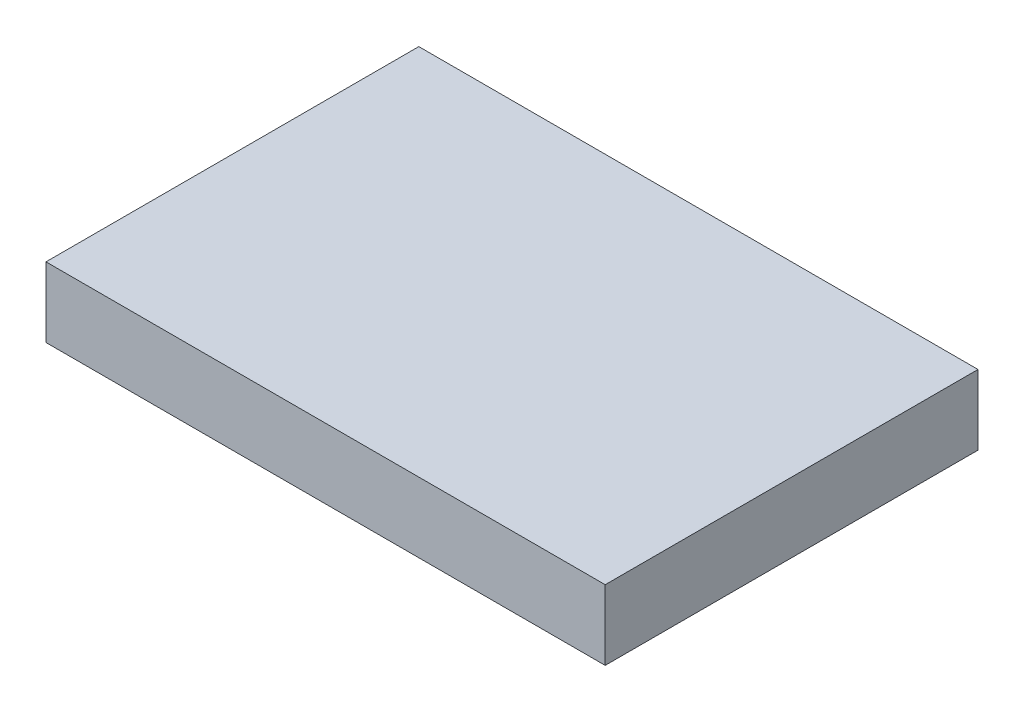
SolidWorks part; units mm, degrees
ref_plane "Front Plane" through (0, 0, 0) normal (0, 0, 1) x (1, 0, 0)
ref_plane "Top Plane" through (0, 0, 0) normal (0, 1, 0) x (1, 0, 0)
ref_plane "Right Plane" through (0, 0, 0) normal (1, 0, 0) x (0, 0, -1)
sketch "FrontSketch" plane through (0, 0, 0) normal (0, 0, 1) x (1, 0, 0)
  line L0 (152.4, 0) -> (-152.4, 0) construction
  line L1 (0, 0) -> (0, 457.2) construction
  line L2 (415.7271, 0) -> (-415.7271, 0) construction
  line L3 (-152.4, 0) -> (-152.4, 38.1) construction
  line L4 (-152.4, 38.1) -> (152.4, 38.1) construction
  line L5 (152.4, 38.1) -> (152.4, 0) construction
  line L6 (-283.3983, 169.5855) -> (472.4692, 169.5855) construction
  spline S0 degree 3 poles (152.4, 38.1) (151.3032, 71.5919) (166.4675, 141.4271) (284.1947, 294.6298) (187.3, 502.2025) (0, 457.2) knots 0 0 0 0 0.177809 0.369856 1 1 1 1
  spline S1 degree 3 poles (22.86, 38.1) (34.1821, 92.9308) (94.0071, 160.8435) (131.317, 308.4431) (55.8008, 387.2291) (0, 378.8263) knots 0 0 0 0 0.38113 0.643813 1 1 1 1
  spline S2 degree 3 poles (66.04, 38.1) (83.0873, 82.1177) (120.2069, 164.1855) (150.9401, 314.436) (52.259, 402.8065) (0, 378.8263) knots 0 0 0 0 0.326005 0.63803 1 1 1 1
  point P4 (0, 0)
  point P26 (190.3118, 169.5855)
  point P28 (116.4485, 169.5855)
  point P29 (85.9889, 169.5855)
  dimension "D1" = 38.1
  dimension "D2" = 304.8
  dimension "D3" = 457.2
  dimension "D4" = 43.18
  dimension "D5" = 86.36
sketch "TopSketch" plane through (0, 0, 0) normal (0, 1, 0) x (1, 0, 0)
  line L1 (-152.4, 101.6) -> (-152.4, -101.6) construction
  line L2 (-152.4, 101.6) -> (152.4, 101.6)
  line L3 (-152.4, 101.6) -> (-152.4, -101.6)
  line L4 (-152.4, -101.6) -> (152.4, -101.6)
  line L5 (152.4, 101.6) -> (152.4, -101.6)
  point P3 (-152.4, 0)
  point P17 (-152.4, 0)
  dimension "D3" = 203.2
extrude "Boss-Extrude1" add sketch "TopSketch" along normal blind 38.1 contours L3 L2 L5 L4
sketch "Sketch4" plane through (0, 38.1, 0) normal (0, 1, 0) x (1, 0, 0)
  line L0 (22.86, 101.6) -> (22.86, -101.6) construction
  line L3 (66.04, 101.6) -> (66.04, -101.6) construction
  arc A0 (22.86, 101.6) -> (22.86, -101.6) centre (-75.0794, 0) cw
  ellipse E0 centre (22.86, 0) end of major axis (152.4, 0) minor radius 101.6 (22.86, -101.6) -> (22.86, 101.6) ccw
  point P3 (66.04, 0)
  point P4 (22.86, 0)
  point P9 (66.04, 0)
  dimension "D1" = 43.18
  dimension "D2" = 203.2
  dimension "D3" = 203.2
sketch3d "3DSketch1"
  line L0 (-283.3983, 169.5855, 0) -> (472.4692, 169.5855, 0) construction
sketch "Sketch5" plane through (0, 169.5855, 0) normal (0, 1, 0) x (1, 0, 0)
  line L0 (85.9685, 76.2) -> (85.9685, -76.2) construction
  line L2 (152.4, 0) -> (-152.4, 0) construction
  line L5 (73.6019, 76.2) -> (73.6019, -76.2) construction
  arc A0 (85.9685, 76.2) -> (85.9685, -76.2) centre (5.9585, 0) cw
  ellipse E0 centre (73.6019, 0) end of major axis (190.3118, 0) minor radius 76.2 (73.6019, -76.2) -> (73.6019, 76.2) ccw
  point P3 (116.4485, 0)
  point P4 (85.9685, 0)
  point P11 (0, 0)
  point P13 (0, 0)
  point P18 (0, 0)
  point P20 (190.3118, 0)
  point P21 (0, 0)
  point P22 (0, 0)
  point P23 (0, 0)
  point P24 (58.9123, 76.2)
  point P25 (120.3176, 76.2)
  point P26 (73.6019, 76.2)
  point P27 (0, 0)
  dimension "D2" = 30.48
  dimension "D1" = 152.4
  dimension "D3" = 152.4
